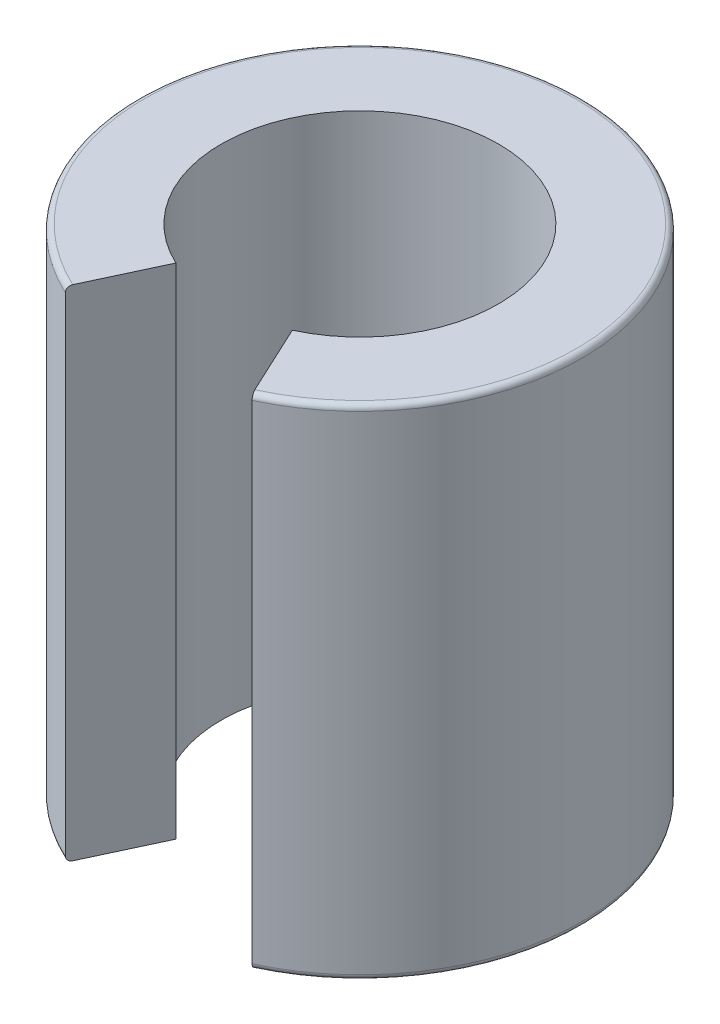
SolidWorks part; units mm, degrees
ref_plane "Front Plane" through (0, 0, 0) normal (0, 0, 1) x (1, 0, 0)
ref_plane "Top Plane" through (0, 0, 0) normal (0, 1, 0) x (1, 0, 0)
ref_plane "Right Plane" through (0, 0, 0) normal (1, 0, 0) x (0, 0, -1)
sketch "Sketch1" plane through (0, 0, 0) normal (0, 1, 0) x (1, 0, 0)
  line L0 (-16.8393, -36.2828) -> (-10.5, -22.6881)
  line L1 (16.8393, -36.2828) -> (10.5, -22.6881)
  line L2 (0, 0) -> (0, -36.2828) construction
  arc A0 (16.8393, -36.2828) -> (-16.8393, -36.2828) centre (0, 0) ccw
  arc A1 (10.5, -22.6881) -> (-10.5, -22.6881) centre (0, 0) ccw
  point P1 (0, 0)
  point P8 (21.8581, -33.4996)
  dimension "D1" = 80
  dimension "D2" = 50
  dimension "D3" = 10.5
  dimension "D4" = 10.5
  dimension "D5" = 25
  dimension "D6" = 25
extrude "Boss-Extrude1" add sketch "Sketch1" along normal blind 90
fillet "Fillet1" radius 1 2 edges at (0, 0, -40) (0, 90, -40)
